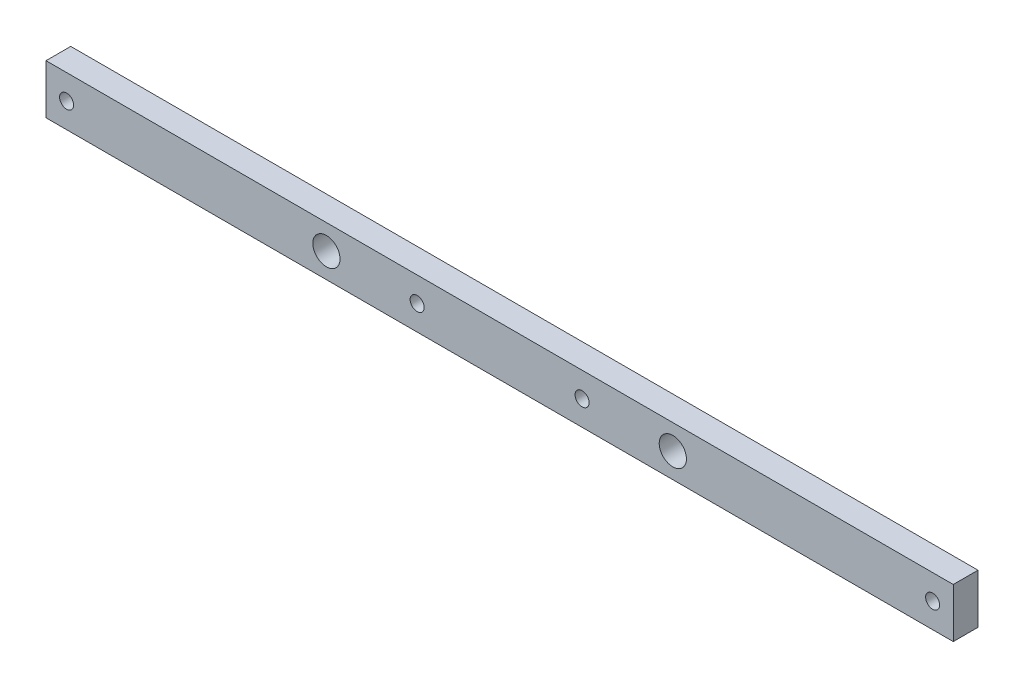
SolidWorks part; units mm, degrees
material "6061-T6 (SS)"
ref_plane "Front Plane" through (0, 0, 0) normal (0, 0, 1) x (1, 0, 0)
ref_plane "Top Plane" through (0, 0, 0) normal (0, 1, 0) x (1, 0, 0)
ref_plane "Right Plane" through (0, 0, 0) normal (1, 0, 0) x (0, 0, -1)
sketch "Sketch1" plane through (0, 0, 0) normal (0, 0, 1) x (1, 0, 0)
  line L1 (-110, -6) -> (110, -6)
  line L2 (-110, -6) -> (-110, 6)
  line L3 (-110, 6) -> (110, 6)
  line L4 (110, -6) -> (110, 6)
  circle A0 centre (-105, 0) radius 1.7
  circle A1 centre (105, 0) radius 1.7
  circle A2 centre (-42, 0) radius 3.3
  circle A3 centre (42, 0) radius 3.3
extrude "Header_Crossbeam" add sketch "Sketch1" along normal blind 6
sketch "Sketch2" plane through (0, 0, 6) normal (0, 0, 1) x (1, 0, 0)
  circle A0 centre (-20, 0) radius 1.7
  circle A1 centre (20, 0) radius 1.7
extrude "Bench_Header_M3_Clearance_Holes_2x_D3p4" cut sketch "Sketch2" against normal blind 6.5
